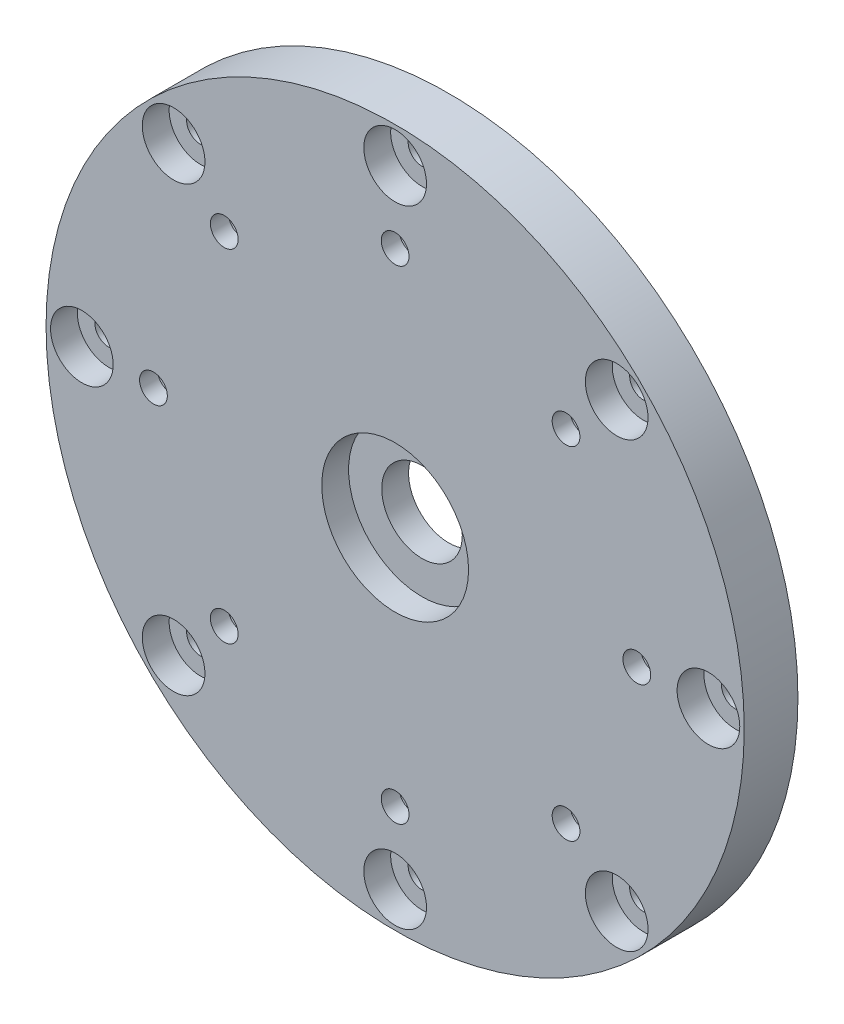
SolidWorks part; units mm, degrees
ref_plane "Front Plane" through (0, 0, 0) normal (0, 0, 1) x (1, 0, 0)
ref_plane "Top Plane" through (0, 0, 0) normal (0, 1, 0) x (1, 0, 0)
ref_plane "Right Plane" through (0, 0, 0) normal (1, 0, 0) x (0, 0, -1)
sketch "Sketch1" plane through (0, 0, 0) normal (0, 0, 1) x (1, 0, 0)
  line L0 (0, 0) -> (-27, 0) construction
  line L1 (0, 0) -> (-35, 0) construction
  circle A1 centre (0, 0) radius 39
  circle A2 centre (-27, 0) radius 1.55
  circle A3 centre (-19.0919, 19.0919) radius 1.55
  circle A4 centre (0, 27) radius 1.55
  circle A5 centre (19.0919, 19.0919) radius 1.55
  circle A6 centre (27, 0) radius 1.55
  circle A7 centre (19.0919, -19.0919) radius 1.55
  circle A8 centre (0, -27) radius 1.55
  circle A9 centre (-19.0919, -19.0919) radius 1.55
  circle A10 centre (0, 0) radius 4.5
  circle A11 centre (-35, 0) radius 1.55
  circle A12 centre (-24.7487, 24.7487) radius 1.55
  circle A13 centre (0, 35) radius 1.55
  circle A14 centre (24.7487, 24.7487) radius 1.55
  circle A15 centre (35, 0) radius 1.55
  circle A16 centre (24.7487, -24.7487) radius 1.55
  circle A17 centre (0, -35) radius 1.55
  circle A18 centre (-24.7487, -24.7487) radius 1.55
  point P21 (0, 0)
  point P39 (0, 0)
  dimension "D1" = 8
  dimension "D2" = 8
extrude "Boss-Extrude2" add sketch "Sketch1" along normal blind 6
sketch "Sketch2" plane through (0, 0, 6) normal (0, 0, 1) x (1, 0, 0)
  circle A0 centre (0, 0) radius 8.2
extrude "Cut-Extrude1" cut sketch "Sketch2" against normal blind 3
sketch "Sketch3" plane through (0, 0, 0) normal (0, 0, -1) x (-1, 0, 0)
  circle A0 centre (0, 27) radius 3.5
  circle A1 centre (19.0919, 19.0919) radius 3.5
  circle A2 centre (27, 0) radius 3.5
  circle A3 centre (19.0919, -19.0919) radius 3.5
  circle A4 centre (0, -27) radius 3.5
  circle A5 centre (-19.0919, -19.0919) radius 3.5
  circle A6 centre (-27, 0) radius 3.5
  circle A7 centre (-19.0919, 19.0919) radius 3.5
  point P19 (0, 0)
  point P37 (0, 0)
  dimension "D1" = 8
extrude "Cut-Extrude2" cut sketch "Sketch3" against normal blind 4
sketch "Sketch4" plane through (0, 0, 6) normal (0, 0, 1) x (1, 0, 0)
  circle A0 centre (-35, 0) radius 3.5
  circle A1 centre (-24.7487, 24.7487) radius 3.5
  circle A2 centre (0, 35) radius 3.5
  circle A3 centre (24.7487, 24.7487) radius 3.5
  circle A4 centre (35, 0) radius 3.5
  circle A5 centre (24.7487, -24.7487) radius 3.5
  circle A6 centre (0, -35) radius 3.5
  circle A7 centre (-24.7487, -24.7487) radius 3.5
  point P19 (0, 0)
  dimension "D1" = 8
extrude "Cut-Extrude3" cut sketch "Sketch4" against normal blind 3
